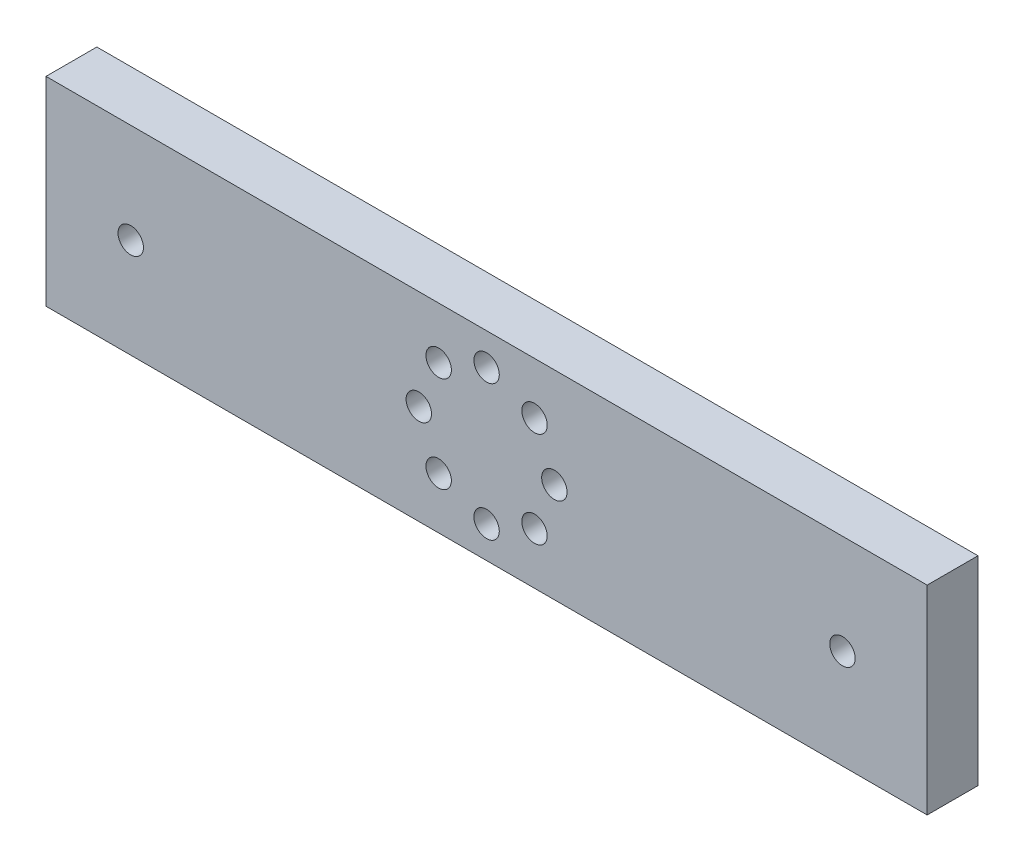
SolidWorks part; units mm, degrees
ref_plane "前视基准面" through (0, 0, 0) normal (0, 0, 1) x (1, 0, 0)
ref_plane "上视基准面" through (0, 0, 0) normal (0, 1, 0) x (1, 0, 0)
ref_plane "右视基准面" through (0, 0, 0) normal (1, 0, 0) x (0, 0, -1)
sketch "草图1" plane through (0, 0, 0) normal (0, 0, 1) x (1, 0, 0)
  line L1 (104, -23.5) -> (-104, -23.5)
  line L2 (104, -23.5) -> (104, 23.5)
  line L3 (104, 23.5) -> (-104, 23.5)
  line L4 (-104, -23.5) -> (-104, 23.5)
  line L5 (104, -23.5) -> (-104, 23.5) construction
  line L6 (104, 23.5) -> (-104, -23.5) construction
  circle A0 centre (16, 0) radius 3
  circle A1 centre (11.3137, -11.3137) radius 3
  circle A2 centre (0, -16) radius 3
  circle A3 centre (-11.3137, -11.3137) radius 3
  circle A4 centre (-16, 0) radius 3
  circle A5 centre (-11.3137, 11.3137) radius 3
  circle A6 centre (0, 16) radius 3
  circle A7 centre (11.3137, 11.3137) radius 3
  circle A8 centre (-84, 0) radius 3
  circle A9 centre (84, 0) radius 3
  point P0 (0, 0)
  dimension "D3" = 6
  dimension "D6" = 6
  dimension "D7" = 6
  dimension "D1" = 208
  dimension "D2" = 47
  dimension "D4" = 16
  dimension "D8" = 20
  dimension "D9" = 20
  dimension "D5" = 8
extrude "凸台-拉伸1" add sketch "草图1" along normal blind 12
